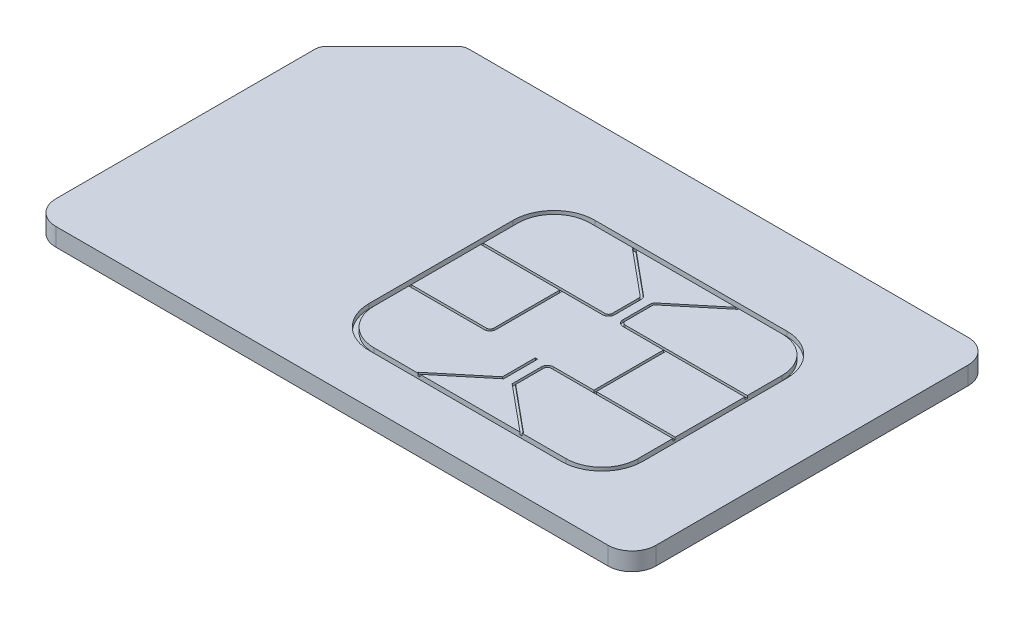
SolidWorks part; units mm, degrees
ref_plane "Front Plane" through (0, 0, 0) normal (0, 0, 1) x (1, 0, 0)
ref_plane "Top Plane" through (0, 0, 0) normal (0, 1, 0) x (1, 0, 0)
ref_plane "Right Plane" through (0, 0, 0) normal (1, 0, 0) x (0, 0, -1)
sketch "Sketch1" plane through (0, 0, 0) normal (0, 1, 0) x (1, 0, 0)
  line L0 (0.1464, 12.1464) -> (2.8536, 14.8536)
  line L1 (1, 0) -> (24, 0)
  line L2 (0, 1) -> (0, 11.7929)
  line L3 (3.2071, 15) -> (24, 15)
  line L4 (25, 1) -> (25, 14)
  arc A0 (24, 0) -> (25, 1) centre (24, 1) ccw
  arc A1 (24, 15) -> (25, 14) centre (24, 14) cw
  arc A2 (1, 0) -> (0, 1) centre (1, 1) cw
  arc A3 (3.2071, 15) -> (2.8536, 14.8536) centre (3.2071, 14.5) ccw
  arc A4 (0, 11.7929) -> (0.1464, 12.1464) centre (0.5, 11.7929) cw
  point P7 (25, 0)
  point P9 (0, 15)
  point P13 (0, 0)
  point P17 (3, 15)
  point P20 (0, 12)
  dimension "D3" = 1
  dimension "D4" = 0.5
  dimension "D1" = 1
  dimension "D2" = 25
extrude "Extrude1" add sketch "Sketch1" along normal blind 0.75
sketch "Sketch2" plane through (0, 0.75, 0) normal (0, 1, 0) x (1, 0, 0)
  line L0 (1, 0) -> (24, 0) construction
  line L1 (12, 11.25) -> (20, 11.25)
  line L2 (10.5, 9.75) -> (10.5, 3.75)
  line L3 (12, 2.25) -> (20, 2.25)
  line L4 (21.5, 9.75) -> (21.5, 3.75)
  line L6 (25, 1) -> (25, 14) construction
  arc A0 (20, 2.25) -> (21.5, 3.75) centre (20, 3.75) ccw
  arc A1 (21.5, 9.75) -> (20, 11.25) centre (20, 9.75) ccw
  arc A2 (12, 2.25) -> (10.5, 3.75) centre (12, 3.75) cw
  arc A3 (10.5, 9.75) -> (12, 11.25) centre (12, 9.75) cw
  point P8 (21.5, 11.25)
  point P11 (10.5, 2.25)
  point P14 (10.5, 11.25)
  dimension "D3" = 1.5
  dimension "D1" = 9
  dimension "D2" = 11
  dimension "D4" = 2.25
  dimension "D5" = 3.5
extrude "Cut-Extrude-Thin1" cut sketch "Sketch2" against normal blind 0.2 thin contours L1 A1 L4 A0 L3 A2 L2 A3 thin type one direction wall 0.2
sketch "Sketch3" plane through (0, 0.75, 0) normal (0, 1, 0) x (1, 0, 0)
  line L0 (10.5, 6.75) -> (21.5, 6.75) construction
  line L1 (10.5, 9.75) -> (10.5, 3.75) construction
  line L2 (21.5, 3.75) -> (21.5, 9.75) construction
  line L3 (16, 11.25) -> (16, 2.25) construction
  line L4 (20, 11.25) -> (12, 11.25) construction
  line L5 (12, 2.25) -> (20, 2.25) construction
  line L6 (10.5, 8.25) -> (15.574, 8.25)
  line L7 (10.5, 9.75) -> (10.5, 3.75) construction
  line L8 (15.774, 8.45) -> (15.774, 9.5519)
  line L9 (15.7017, 9.7059) -> (13.8383, 11.25)
  line L10 (20, 11.25) -> (12, 11.25) construction
  line L11 (16.2983, 9.7059) -> (18.1617, 11.25)
  line L12 (16.226, 8.45) -> (16.226, 9.5519)
  line L13 (21.5, 8.25) -> (16.426, 8.25)
  line L14 (21.5, 5.25) -> (16.426, 5.25)
  line L15 (16.226, 5.05) -> (16.226, 3.854)
  line L16 (16.226, 3.854) -> (18.1617, 2.25)
  line L17 (15.774, 3.854) -> (13.8383, 2.25)
  line L18 (15.774, 5.25) -> (15.774, 3.854)
  line L19 (10.5, 5.25) -> (13.6383, 5.25)
  line L20 (13.8383, 8.25) -> (13.8383, 5.45)
  line L21 (18.1617, 8.25) -> (18.1617, 5.25)
  arc A0 (16.226, 5.05) -> (16.426, 5.25) centre (16.426, 5.05) cw
  arc A1 (16.226, 8.45) -> (16.426, 8.25) centre (16.426, 8.45) ccw
  arc A2 (16.226, 9.5519) -> (16.2983, 9.7059) centre (16.426, 9.5519) cw
  arc A3 (15.7017, 9.7059) -> (15.774, 9.5519) centre (15.574, 9.5519) cw
  arc A4 (15.774, 8.45) -> (15.574, 8.25) centre (15.574, 8.45) cw
  arc A5 (13.8383, 5.45) -> (13.6383, 5.25) centre (13.6383, 5.45) cw
  point P38 (16.226, 5.25)
  point P41 (16.226, 8.25)
  point P44 (16.226, 9.646)
  point P47 (15.774, 9.646)
  point P50 (15.774, 8.25)
  point P53 (13.8383, 5.25)
  dimension "D2" = 0.2
  dimension "D1" = 3
  dimension "D3" = 5.274
  dimension "D4" = 3.3383
  dimension "D5" = 1.4559
extrude "Cut-Extrude-Thin6" cut sketch "Sketch3" against normal blind 0.1 thin thin type mid plane wall 0.1
